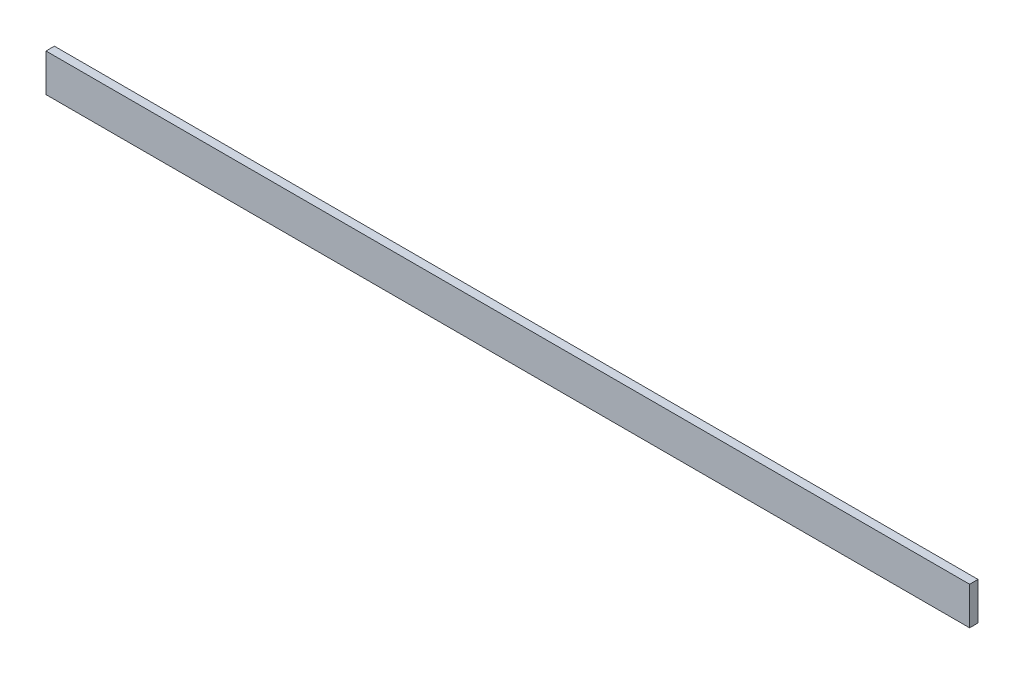
SolidWorks part; units mm, degrees
ref_plane "Plan de face" through (0, 0, 0) normal (0, 0, 1) x (1, 0, 0)
ref_plane "Plan de dessus" through (0, 0, 0) normal (0, 1, 0) x (1, 0, 0)
ref_plane "Plan de droite" through (0, 0, 0) normal (1, 0, 0) x (0, 0, -1)
sketch "Esquisse1" plane through (0, 0, 0) normal (0, 0, 1) x (1, 0, 0)
  line L1 (-123.6211, 34.7998) -> (2076.3789, 34.7998)
  line L2 (-123.6211, 34.7998) -> (-123.6211, -55.2002)
  line L3 (-123.6211, -55.2002) -> (2076.3789, -55.2002)
  line L4 (2076.3789, 34.7998) -> (2076.3789, -55.2002)
  dimension "D1" = 2200
  dimension "D2" = 90
extrude "Boss.-Extru.1" add sketch "Esquisse1" along normal blind 20
